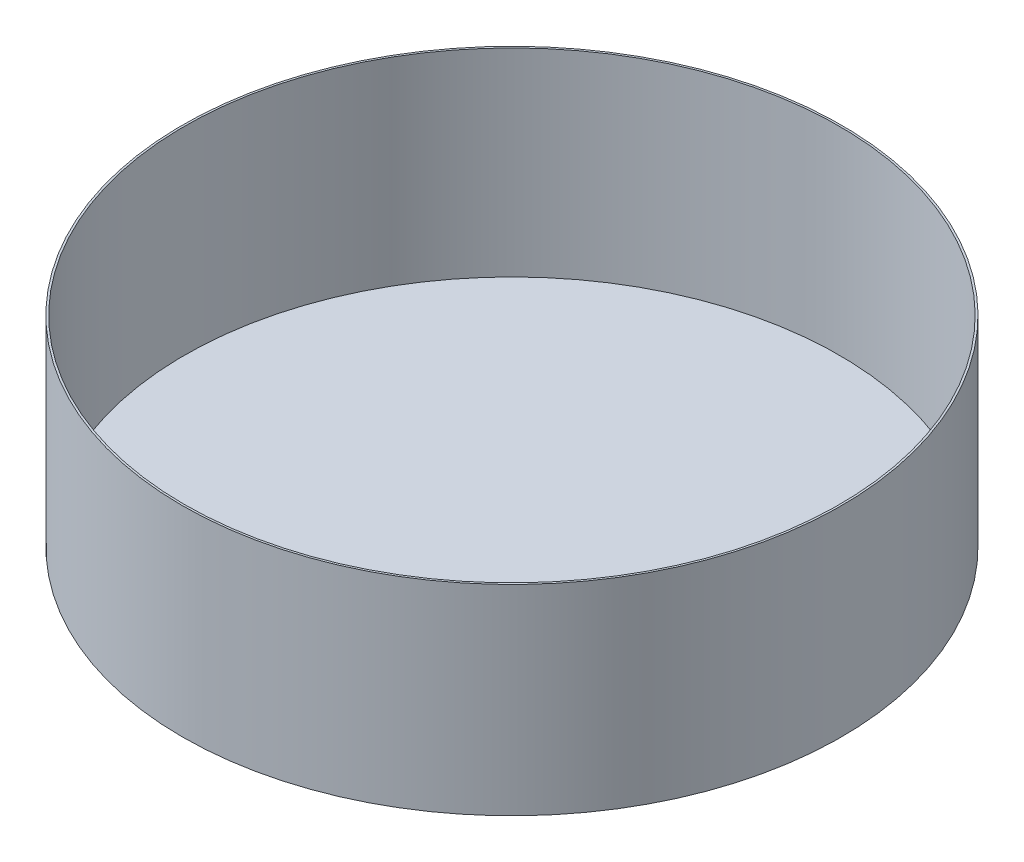
SolidWorks part; units mm, degrees
ref_plane "Front" through (0, 0, 0) normal (0, 0, 1) x (1, 0, 0)
ref_plane "Top" through (0, 0, 0) normal (0, 1, 0) x (1, 0, 0)
ref_plane "Right" through (0, 0, 0) normal (1, 0, 0) x (0, 0, -1)
sketch "Sketch1" plane through (0, 0, 0) normal (0, 1, 0) x (1, 0, 0)
  circle A0 centre (0, 0) radius 41.125
  dimension "D1" = 82.25
extrude "Boss-Extrude1" add sketch "Sketch1" along normal blind 25
shell "Shell1" thickness 0.25
